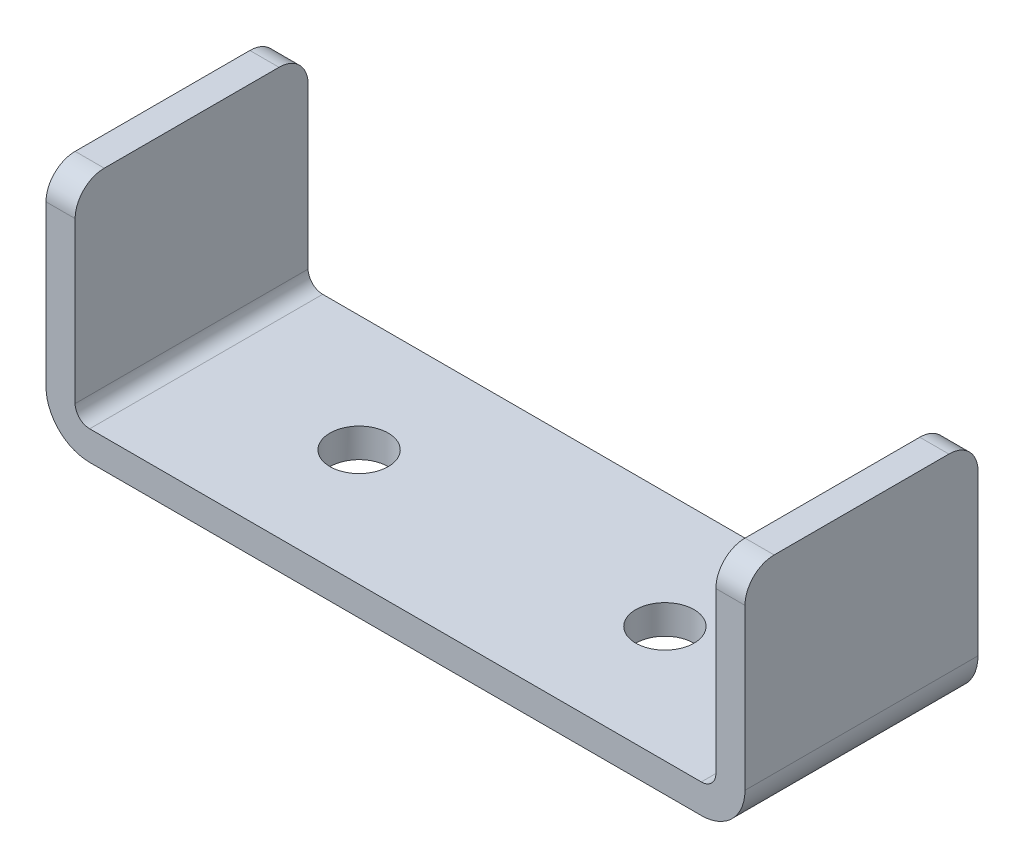
SolidWorks part; units mm, degrees
ref_plane "Front Plane" through (0, 0, 0) normal (0, 0, 1) x (1, 0, 0)
ref_plane "Top Plane" through (0, 0, 0) normal (0, 1, 0) x (1, 0, 0)
ref_plane "Right Plane" through (0, 0, 0) normal (1, 0, 0) x (0, 0, -1)
sketch "Sketch1" plane through (0, 0, 0) normal (0, 0, 1) x (1, 0, 0)
  line L0 (0, 25.4) -> (0, 4.7625)
  line L1 (4.7625, 0) -> (71.4375, 0)
  line L2 (76.2, 4.7625) -> (76.2, 25.4)
  arc A0 (0, 4.7625) -> (4.7625, 0) centre (4.7625, 4.7625) ccw
  arc A1 (71.4375, 0) -> (76.2, 4.7625) centre (71.4375, 4.7625) ccw
  point P7 (0, 0)
  point P10 (76.2, 0)
  dimension "D3" = 4.7625
  dimension "tab length" = 25.4
  dimension "overall length" = 76.2
extrude "Extrude-Thin1" add sketch "Sketch1" against normal blind 25.4 thin thin type one direction reverse wall 3.175
fillet "Fillet1" radius 3.175 4 edges at (74.6125, 25.4, 0) (74.6125, 25.4, -25.4) (1.5875, 25.4, -25.4) (1.5875, 25.4, 0)
ref_plane "Plane2" through (0, 3.175, 0) normal (0, 1, 0) x (-1, 0, 0)
sketch "Sketch2" plane through (0, 3.175, 0) normal (0, 1, 0) x (-1, 0, 0)
  line L0 (-4.7625, -12.7) -> (-38.1, -12.7) construction
  line L1 (-4.7625, -25.4) -> (-4.7625, 0) construction
  line L3 (-38.1, 0) -> (-38.1, -25.4) construction
  line L4 (-4.7625, 0) -> (-71.4375, 0) construction
  line L5 (-4.7625, -25.4) -> (-71.4375, -25.4) construction
  line L6 (-21.4312, -12.7) -> (-21.4312, 0) construction
  circle A0 centre (-21.4312, -12.7) radius 3.175
  circle A1 centre (-54.7688, -12.7) radius 3.175
  dimension "thru hole diam" = 6.35
extrude "Extrude1" cut sketch "Sketch2" against normal blind 25.4
